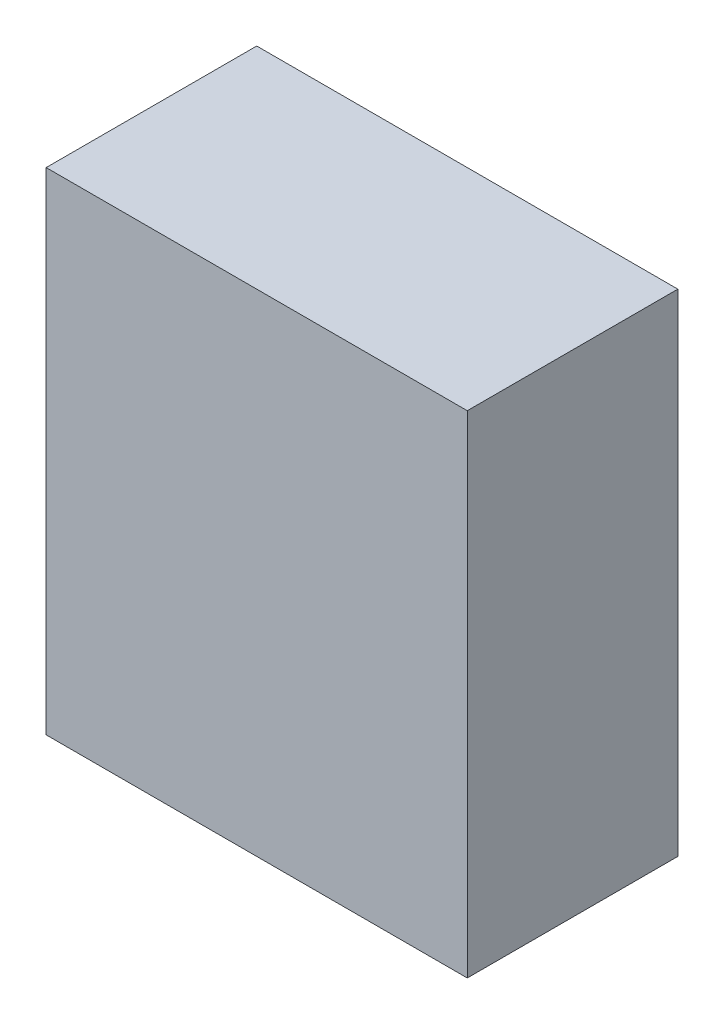
SolidWorks part; units mm, degrees
material "ABS PC"
ref_plane "Front Plane" through (0, 0, 0) normal (0, 0, 1) x (1, 0, 0)
ref_plane "Top Plane" through (0, 0, 0) normal (0, 1, 0) x (1, 0, 0)
ref_plane "Right Plane" through (0, 0, 0) normal (1, 0, 0) x (0, 0, -1)
sketch "Sketch1" plane through (0, 0, 0) normal (0, 0, 1) x (1, 0, 0)
  line L1 (-30, 35) -> (30, 35)
  line L2 (-30, 35) -> (-30, -35)
  line L3 (-30, -35) -> (30, -35)
  line L4 (30, 35) -> (30, -35)
  line L5 (0, -35) -> (0, 35) construction
  line L6 (-30, 0) -> (30, 0) construction
  point P0 (0, 0)
  dimension "D1" = 60
  dimension "D2" = 70
extrude "Boss-Extrude1" add sketch "Sketch1" along normal blind 30
shell "Shell1" thickness 2.5
sketch "Sketch2" plane through (0, 0, 30) normal (0, 0, 1) x (1, 0, 0)
  line L1 (-30, 35) -> (30, 35)
  line L2 (-30, 35) -> (-30, -35)
  line L3 (-30, -35) -> (30, -35)
  line L4 (30, 35) -> (30, -35)
  line L5 (0, -35) -> (0, 35) construction
  line L6 (-30, 0) -> (30, 0) construction
  point P0 (0, 0)
